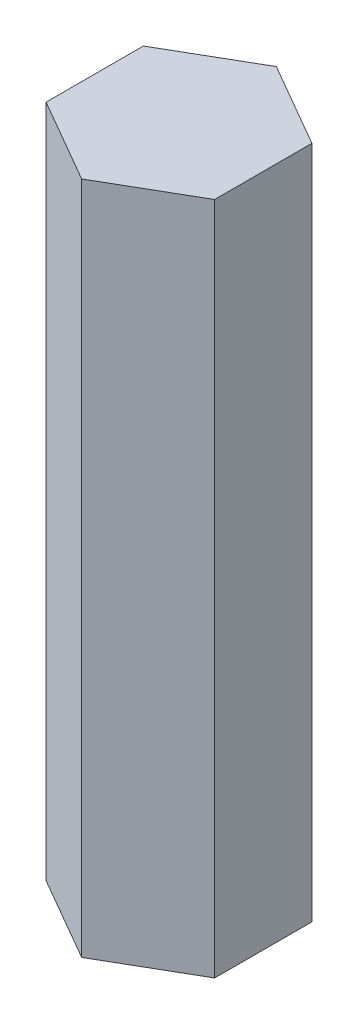
SolidWorks part; units mm, degrees
ref_plane "Front Plane" through (0, 0, 0) normal (0, 0, 1) x (1, 0, 0)
ref_plane "Top Plane" through (0, 0, 0) normal (0, 1, 0) x (1, 0, 0)
ref_plane "Right Plane" through (0, 0, 0) normal (1, 0, 0) x (0, 0, -1)
sketch "Sketch1" plane through (0, 0, 0) normal (0, 1, 0) x (1, 0, 0)
  line L1 (2.5, -1.4434) -> (2.5, 1.4434)
  line L2 (2.5, 1.4434) -> (0, 2.8868)
  line L3 (0, 2.8868) -> (-2.5, 1.4434)
  line L4 (-2.5, 1.4434) -> (-2.5, -1.4434)
  line L5 (-2.5, -1.4434) -> (0, -2.8868)
  line L6 (0, -2.8868) -> (2.5, -1.4434)
  circle A0 centre (0, 0) radius 2.5 construction
  point P1 (-2.3427, -1.6867)
  dimension "D1" = 5
extrude "Boss-Extrude1" add sketch "Sketch1" along normal blind 20
